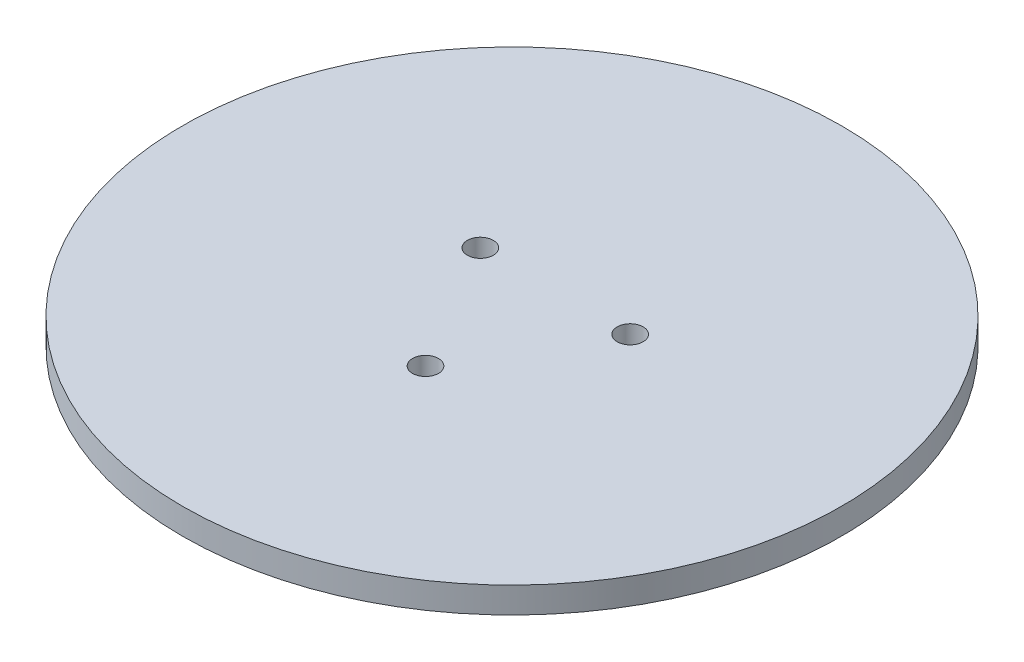
SolidWorks part; units mm, degrees
material "Oak"
ref_plane "Front Plane" through (0, 0, 0) normal (0, 0, 1) x (1, 0, 0)
ref_plane "Top Plane" through (0, 0, 0) normal (0, 1, 0) x (1, 0, 0)
ref_plane "Right Plane" through (0, 0, 0) normal (1, 0, 0) x (0, 0, -1)
sketch "Sketch1" plane through (0, 0, 0) normal (0, 1, 0) x (1, 0, 0)
  circle A0 centre (0, 0) radius 38.1
  dimension "D1" = 76.2
extrude "Boss-Extrude1" add sketch "Sketch1" along normal blind 3
sketch "Sketch3" plane through (0, 3, 0) normal (0, 1, 0) x (1, 0, 0)
  line L0 (0, 0) -> (0, -10)
  line L1 (0, 0) -> (8.6603, 5)
  line L2 (0, 0) -> (-8.6603, 5)
  circle A3 centre (-8.6603, 5) radius 1.5
  circle A4 centre (8.6603, 5) radius 1.5
  circle A5 centre (0, -10) radius 1.5
  dimension "D6" = 3
  dimension "D7" = 3
  dimension "D8" = 3
  dimension "D1" = 10
  dimension "D2" = 10
  dimension "D3" = 10
  dimension "D4" = 120
  dimension "D5" = 120
extrude "Cut-Extrude2" cut sketch "Sketch3" against normal through all contours A5 | A4 | A3
